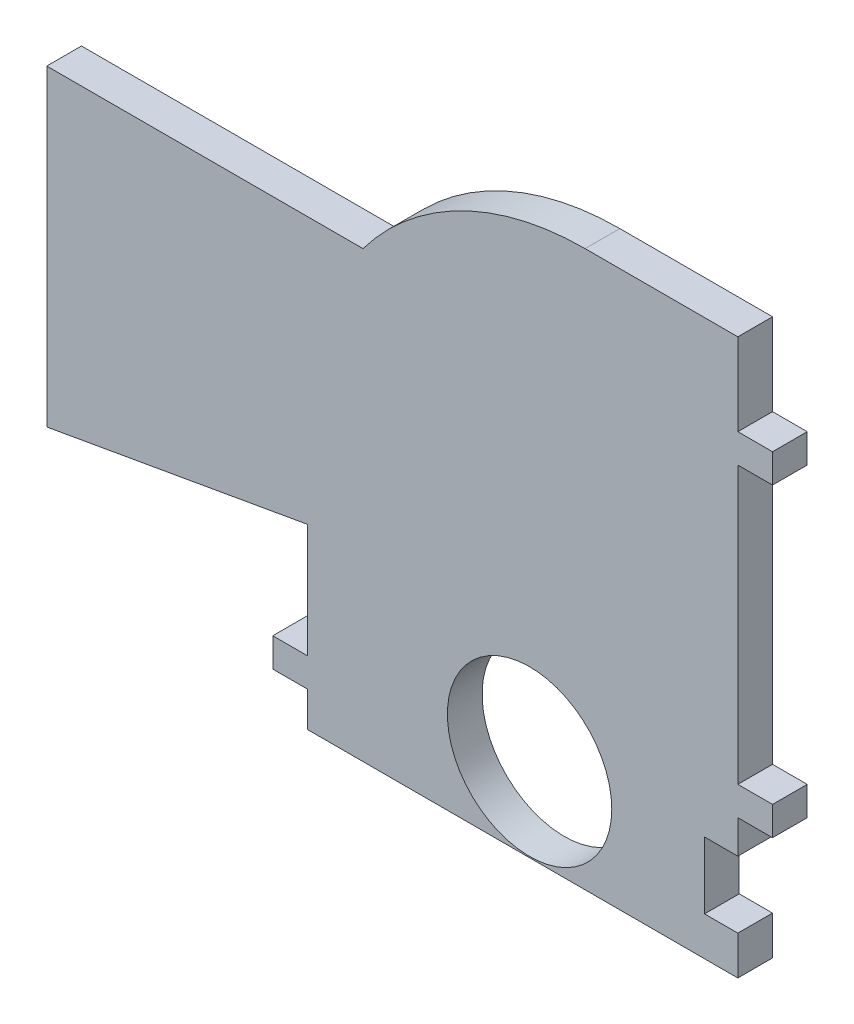
SolidWorks part; units mm, degrees
material "Balsa"
ref_plane "Front Plane" through (0, 0, 0) normal (0, 0, 1) x (1, 0, 0)
ref_plane "Top Plane" through (0, 0, 0) normal (0, 1, 0) x (1, 0, 0)
ref_plane "Right Plane" through (0, 0, 0) normal (1, 0, 0) x (0, 0, -1)
sketch "Sketch1" plane through (0, 0, 0) normal (0, 0, 1) x (1, 0, 0)
  line L0 (0, -1000.1535) -> (0, 48999.8465) construction
  line L1 (-7.62, 16.51) -> (-22.0849, 16.51)
  line L2 (-1000, 0) -> (49000, 0) construction
  line L3 (9.525, 16.51) -> (11.1125, 16.51)
  line L4 (2.54, 21.59) -> (9.525, 21.59)
  line L5 (-10.16, 8.89) -> (-10.16, -3.81)
  line L6 (-10.16, -3.81) -> (9.525, -3.81)
  line L7 (9.525, 21.59) -> (9.525, -3.81)
  line L8 (-11.7475, -2.2098) -> (-10.16, -2.2098)
  line L9 (-11.7475, -2.2098) -> (-11.7475, -0.889)
  line L10 (-11.7475, -0.889) -> (-10.16, -0.889)
  line L11 (-10.16, -2.2098) -> (-10.16, -0.889)
  line L12 (9.525, 2.54) -> (11.1125, 2.54)
  line L13 (9.525, 2.54) -> (9.525, 3.8608)
  line L14 (9.525, 3.8608) -> (11.1125, 3.8608)
  line L15 (11.1125, 2.54) -> (11.1125, 3.8608)
  line L16 (9.525, 16.51) -> (9.525, 17.8308)
  line L17 (9.525, 17.8308) -> (11.1125, 17.8308)
  line L18 (11.1125, 16.51) -> (11.1125, 17.8308)
  line L20 (-22.0849, 2.212) -> (-10.16, 4.318)
  line L22 (-22.0849, 13.081) -> (-22.0849, 4.699)
  line L26 (-22.0849, 13.081) -> (-22.0849, 16.51)
  line L27 (9.525, 1.016) -> (8.001, 1.016)
  line L28 (9.525, 1.016) -> (9.525, -2.032)
  line L29 (9.525, -2.032) -> (8.001, -2.032)
  line L30 (8.001, 1.016) -> (8.001, -2.032)
  line L31 (-22.0849, 4.699) -> (-22.0849, 2.212)
  circle A0 centre (0, 0) radius 3.7592
  arc A3 (2.54, 21.59) -> (-10.16, 8.89) centre (2.54, 8.89) ccw
  dimension "D1" = 7.5184
  dimension "D4" = 3.81
  dimension "D3" = 3.7592
  dimension "D5" = 1.5875
  dimension "D9" = 12.7
  dimension "D10" = 1.5875
  dimension "D18" = 11.9249
  dimension "D2" = 25.4
  dimension "D6" = 9.525
  dimension "D7" = 1.3208
  dimension "D8" = 19.685
  dimension "D11" = 2.54
  dimension "D12" = 1.3208
  dimension "D13" = 1.3208
  dimension "D14" = 1.5875
  dimension "D15" = 1.524
  dimension "D16" = 1.016
  dimension "D17" = 3.048
  dimension "D19" = 5.08
  dimension "D20" = 8.128
  dimension "D21" = 14.298
  dimension "D22" = 5.207
extrude "Boss-Extrude1" add sketch "Sketch1" along normal blind 1.5875
move or copy body "Body-Move/Copy1" [suppressed] bodies to move or copy 101
